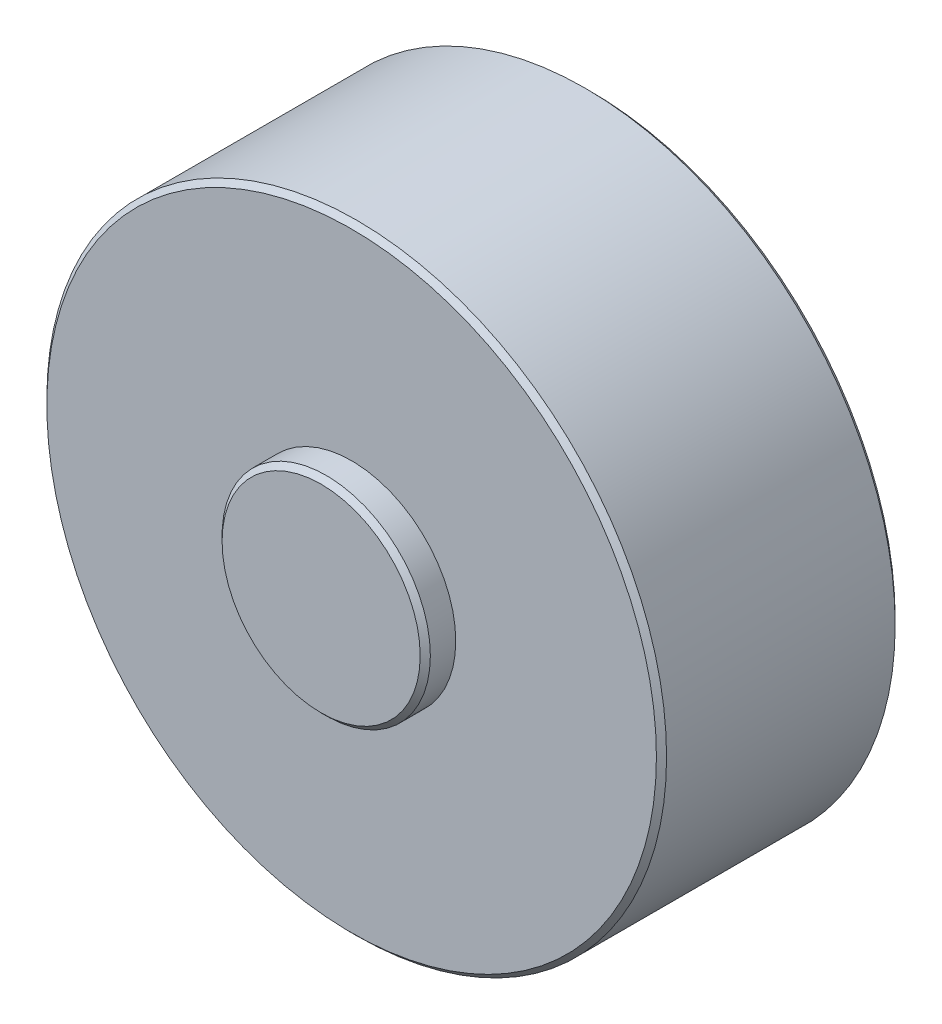
SolidWorks part; units mm, degrees
ref_plane "前视基准面" through (0, 0, 0) normal (0, 0, 1) x (1, 0, 0)
ref_plane "上视基准面" through (0, 0, 0) normal (0, 1, 0) x (1, 0, 0)
ref_plane "右视基准面" through (0, 0, 0) normal (1, 0, 0) x (0, 0, -1)
sketch "草图1" plane through (0, 0, 0) normal (0, 0, 1) x (1, 0, 0)
  circle A0 centre (0, 0) radius 61
  dimension "D1" = 122
extrude "凸台-拉伸1" add sketch "草图1" along normal blind 47
sketch "草图2" plane through (0, 0, 47) normal (0, 0, 1) x (1, 0, 0)
  circle A0 centre (0, 0) radius 20.5
  dimension "D1" = 41
extrude "凸台-拉伸2" add sketch "草图2" along normal blind 6
chamfer "倒角1" distance 1 angle 45 3 edges at (61, 0, 0) (61, 0, 47) (20.5, 0, 53)
